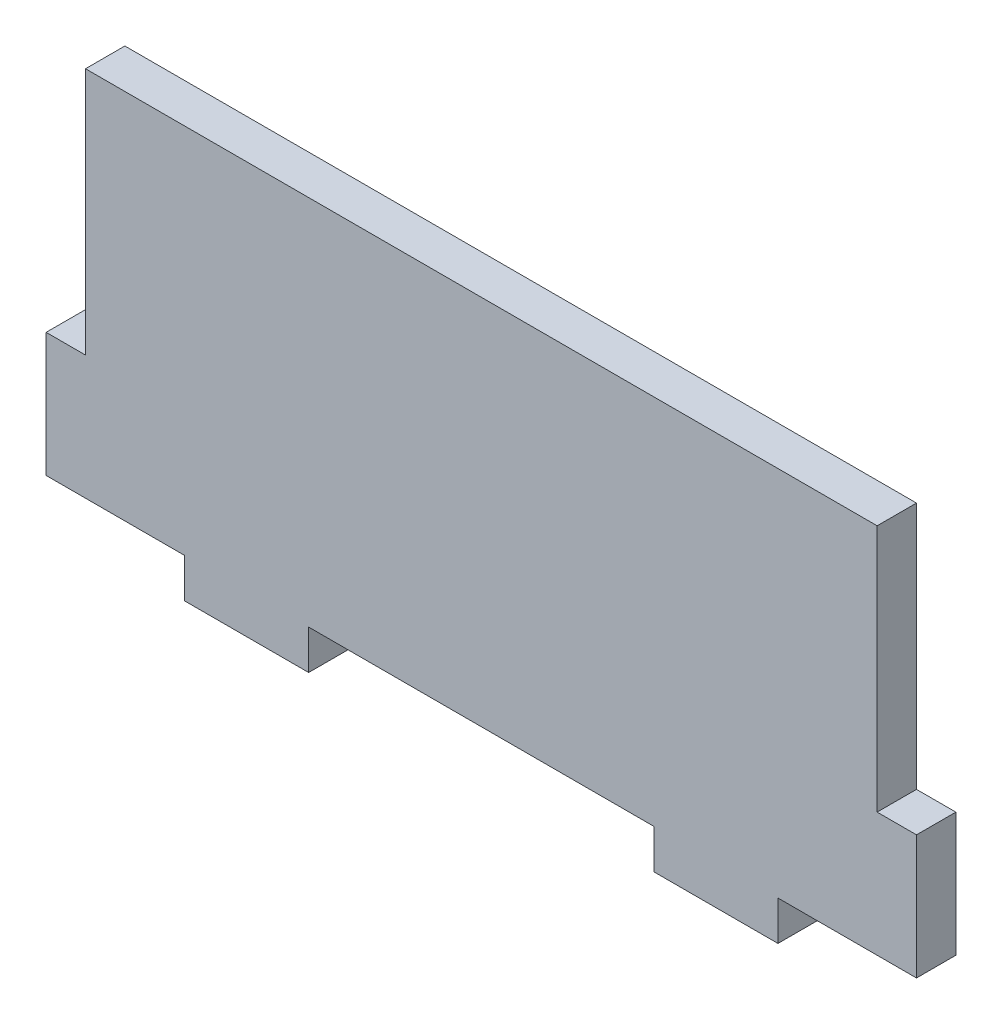
SolidWorks part; units mm, degrees
ref_plane "Front Plane" through (0, 0, 0) normal (0, 0, 1) x (1, 0, 0)
ref_plane "Top Plane" through (0, 0, 0) normal (0, 1, 0) x (1, 0, 0)
ref_plane "Right Plane" through (0, 0, 0) normal (1, 0, 0) x (0, 0, -1)
sketch "Sketch3" plane through (0, 0, 0) normal (0, 0, 1) x (1, 0, 0)
  line L0 (0, -55) -> (0, 55) construction
  line L1 (-127.7, -60) -> (127.7, -60)
  line L2 (-127.7, -60) -> (-127.7, 60)
  line L3 (-127.7, 60) -> (127.7, 60)
  line L4 (127.7, -60) -> (127.7, 60)
  line L5 (-127.7, -60) -> (127.7, 60) construction
  line L6 (-127.7, 60) -> (127.7, -60) construction
  line L7 (127.7, -60) -> (140.4, -60)
  line L8 (127.7, -60) -> (127.7, -20)
  line L9 (127.7, -20) -> (140.4, -20)
  line L10 (140.4, -60) -> (140.4, -20)
  line L11 (-127.7, -20) -> (-140.4, -20)
  line L12 (-140.4, -60) -> (-140.4, -20)
  line L13 (-127.7, -60) -> (-140.4, -60)
  line L14 (-127.7, -60) -> (-127.7, -20)
  line L15 (95.7, -72.7) -> (55.7, -72.7)
  line L16 (-95.7, -60) -> (-55.7, -60)
  line L17 (-95.7, -60) -> (-95.7, -72.7)
  line L18 (-95.7, -72.7) -> (-55.7, -72.7)
  line L19 (-55.7, -60) -> (-55.7, -72.7)
  line L20 (55.7, -60) -> (55.7, -72.7)
  line L21 (95.7, -60) -> (55.7, -60)
  line L22 (95.7, -60) -> (95.7, -72.7)
  point P0 (0, 0)
  dimension "D1" = 120
  dimension "D2" = 255.4
  dimension "D3" = 12.7
  dimension "D4" = 40
  dimension "D5" = 12.7
  dimension "D6" = 40
  dimension "D7" = 32
extrude "Boss-Extrude1" add sketch "Sketch3" along normal blind 12.7 contours L1 L4 L3 L2 | L13 L2 L11 L12 | L19 L1 L17 L18 | L22 L1 L20 L15 | L7 L10 L9 L4
